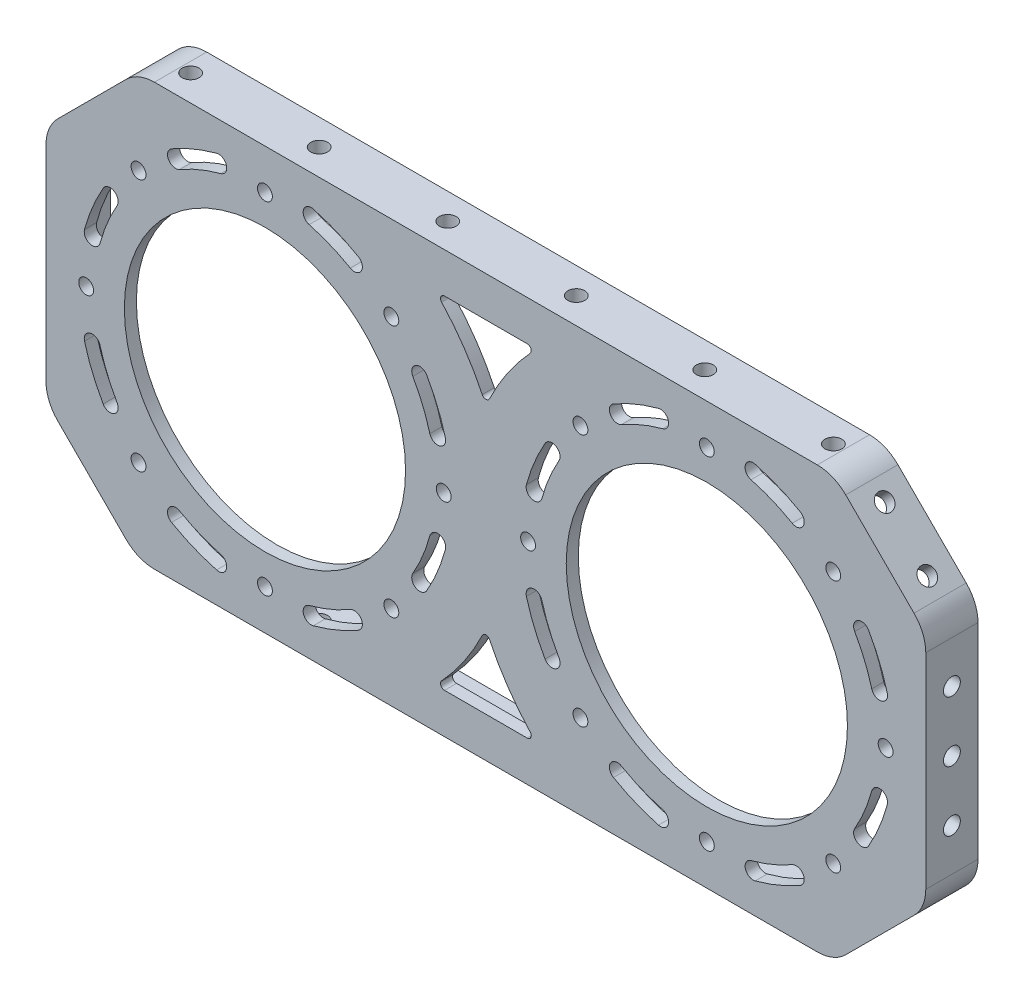
SolidWorks part; units mm, degrees
material "6061 合金"
ref_plane "前视基准面" through (0, 0, 0) normal (0, 0, 1) x (1, 0, 0)
ref_plane "上视基准面" through (0, 0, 0) normal (0, 1, 0) x (1, 0, 0)
ref_plane "右视基准面" through (0, 0, 0) normal (1, 0, 0) x (0, 0, -1)
other "Configuration Table"
sketch "草图1" plane through (0, 0, 0) normal (0, 0, 1) x (1, 0, 0)
  line L0 (-125.5479, 60.1826) -> (-125.5479, -59.8174)
  line L1 (-125.5479, -59.8174) -> (124.4521, -59.8174)
  line L2 (124.4521, -59.8174) -> (124.4521, 60.1826)
  line L3 (124.4521, 60.1826) -> (-125.5479, 60.1826)
  circle A0 centre (54.4521, 42.6826) radius 1.85
  circle A1 centre (85.9183, 31.6489) radius 1.85
  circle A2 centre (98.9521, 0.1826) radius 1.85
  circle A3 centre (85.9183, -31.2836) radius 1.85
  circle A4 centre (22.9858, -31.2836) radius 1.85
  circle A5 centre (22.9858, 31.6489) radius 1.85
  circle A6 centre (54.4521, -42.3174) radius 1.85
  circle A7 centre (9.9521, 0.1826) radius 1.85
  circle A8 centre (54.4521, 0.1826) radius 35
  circle A9 centre (-55.5479, 0.1826) radius 35
  circle A10 centre (-87.0142, 31.6489) radius 1.85
  circle A11 centre (-11.0479, 0.1826) radius 1.85
  circle A12 centre (-55.5479, 42.6826) radius 1.85
  circle A13 centre (-24.0817, 31.6489) radius 1.85
  circle A14 centre (-24.0817, -31.2836) radius 1.85
  circle A15 centre (-55.5479, -42.3174) radius 1.85
  circle A16 centre (-87.0142, -31.2836) radius 1.85
  circle A17 centre (-100.0479, 0.1826) radius 1.85
extrude "凸台-拉伸1" add sketch "草图1" along normal blind 3
sketch "草图2" plane through (0, 0, 3) normal (0, 0, 1) x (1, 0, 0)
  line L0 (-0.5479, 60.1826) -> (-0.5479, -59.8174) construction
  line L1 (-87.1936, 52.6826) -> (-110.0479, 29.8283)
  line L2 (-110.0479, -52.3174) -> (108.9521, -52.3174)
  line L3 (-110.0479, -52.3174) -> (-110.0479, 52.6826)
  line L4 (124.4521, 60.1826) -> (-125.5479, 60.1826)
  line L5 (-125.5479, 60.1826) -> (-125.5479, -59.8174)
  line L6 (-125.5479, -59.8174) -> (124.4521, -59.8174)
  line L7 (124.4521, -59.8174) -> (124.4521, 60.1826)
  line L8 (124.4521, 60.1826) -> (-125.5479, 60.1826)
  line L9 (-125.5479, 60.1826) -> (-125.5479, -59.8174)
  line L10 (-125.5479, -59.8174) -> (124.4521, -59.8174)
  line L11 (124.4521, -59.8174) -> (124.4521, 60.1826)
  line L12 (-110.0479, 52.6826) -> (108.9521, 52.6826)
  line L13 (108.9521, -52.3174) -> (108.9521, 52.6826)
  line L14 (-0.5479, 52.6826) -> (-0.5479, -52.3174) construction
  line L15 (-110.0479, 0.1826) -> (108.9521, 0.1826) construction
  line L16 (-110.0479, -29.4631) -> (-87.1936, -52.3174)
  line L17 (86.0978, 52.6826) -> (108.9521, 29.8283)
  line L18 (108.9521, -29.4631) -> (86.0978, -52.3174)
  circle A0 centre (-55.5479, 42.6826) radius 1.85 construction
  circle A1 centre (-55.5479, -42.3174) radius 1.85 construction
  circle A2 centre (-100.0479, 0.1826) radius 1.85 construction
  circle A3 centre (-87.0142, 31.6489) radius 1.85 construction
  circle A4 centre (-87.0142, -31.2836) radius 1.85 construction
  circle A5 centre (85.9183, 31.6489) radius 1.85 construction
  circle A6 centre (85.9183, -31.2836) radius 1.85 construction
  point P6 (-0.5479, 0.1826)
  line M23 (124.4521, 60.1826) -> (-125.5479, 60.1826)
  line M24 (-125.5479, 60.1826) -> (-125.5479, -59.8174)
  line M25 (-125.5479, -59.8174) -> (124.4521, -59.8174)
  line M26 (124.4521, -59.8174) -> (124.4521, 60.1826)
  dimension "D2" = 10
  dimension "D4" = 10
  dimension "D6" = 15
  dimension "D10" = 15
  dimension "D3" = 10
  dimension "D5" = 45
  dimension "D7" = 45
  dimension "D8" = 45
  dimension "D9" = 45
  dimension "D11" = 15
  dimension "D12" = 15
  dimension "D1" = 0
extrude "切除-拉伸1" cut sketch "草图2" against normal through all contours L13 L2 L3 L12 M26 M23 M24 M25 | L12 L3 L1 | L16 L3 L2 | L13 L18 L2 | L12 L17 L13
sketch "草图3" plane through (0, 0, 0) normal (0, 0, -1) x (-1, 0, 0)
  line L0 (-105.9521, 28.5857) -> (-105.9521, -28.2204)
  line L1 (-105.9521, -28.2204) -> (-84.8551, -49.3174)
  line L2 (-84.8551, -49.3174) -> (85.951, -49.3174)
  line L3 (85.951, -49.3174) -> (107.0479, -28.2204)
  line L4 (107.0479, -28.2204) -> (107.0479, 28.5857)
  line L5 (107.0479, 28.5857) -> (85.951, 49.6826)
  line L6 (85.951, 49.6826) -> (-84.8551, 49.6826)
  line L7 (-84.8551, 49.6826) -> (-105.9521, 28.5857)
  line L8 (-108.9521, 29.8283) -> (-108.9521, -29.4631)
  line L9 (-108.9521, -29.4631) -> (-86.0978, -52.3174)
  line L10 (-86.0978, -52.3174) -> (87.1936, -52.3174)
  line L11 (87.1936, -52.3174) -> (110.0479, -29.4631)
  line L12 (110.0479, -29.4631) -> (110.0479, 29.8283)
  line L13 (110.0479, 29.8283) -> (87.1936, 52.6826)
  line L14 (87.1936, 52.6826) -> (-86.0978, 52.6826)
  line L15 (-86.0978, 52.6826) -> (-108.9521, 29.8283)
  line L16 (-108.9521, 29.8283) -> (-108.9521, -29.4631)
  line L17 (-108.9521, -29.4631) -> (-86.0978, -52.3174)
  line L18 (-86.0978, -52.3174) -> (87.1936, -52.3174)
  line L19 (87.1936, -52.3174) -> (110.0479, -29.4631)
  line L20 (110.0479, -29.4631) -> (110.0479, 29.8283)
  line L21 (110.0479, 29.8283) -> (87.1936, 52.6826)
  line L22 (87.1936, 52.6826) -> (-86.0978, 52.6826)
  line L23 (-86.0978, 52.6826) -> (-108.9521, 29.8283)
  dimension "D1" = 0
  dimension "D2" = 3
extrude "凸台-拉伸2" add sketch "草图3" along normal blind 10
sketch "草图5" plane through (0, 0, 0) normal (0, 0, -1) x (-1, 0, 0)
  line L8 (85.951, 49.6826) -> (-84.8551, 49.6826)
  line L9 (-84.8551, 49.6826) -> (-105.9521, 28.5857)
  line L10 (-105.9521, 28.5857) -> (-105.9521, -28.2204)
  line L11 (-105.9521, -28.2204) -> (-84.8551, -49.3174)
  line L12 (-84.8551, -49.3174) -> (85.951, -49.3174)
  line L13 (85.951, -49.3174) -> (107.0479, -28.2204)
  line L14 (107.0479, -28.2204) -> (107.0479, 28.5857)
  line L15 (107.0479, 28.5857) -> (85.951, 49.6826)
  line L16 (85.951, 49.6826) -> (-84.8551, 49.6826)
  line L17 (-84.8551, 49.6826) -> (-105.9521, 28.5857)
  line L18 (-105.9521, 28.5857) -> (-105.9521, -28.2204)
  line L19 (-105.9521, -28.2204) -> (-84.8551, -49.3174)
  line L20 (-84.8551, -49.3174) -> (85.951, -49.3174)
  line L21 (85.951, -49.3174) -> (107.0479, -28.2204)
  line L22 (107.0479, -28.2204) -> (107.0479, 28.5857)
  line L23 (107.0479, 28.5857) -> (85.951, 49.6826)
  circle A1 centre (-54.4521, 42.6826) radius 1.85
  circle A2 centre (-54.4521, 42.6826) radius 1.85
  circle A3 centre (-85.9183, 31.6489) radius 1.85
  circle A4 centre (-85.9183, 31.6489) radius 1.85
  circle A5 centre (-98.9521, 0.1826) radius 1.85
  circle A6 centre (-98.9521, 0.1826) radius 1.85
  circle A7 centre (-85.9183, -31.2836) radius 1.85
  circle A8 centre (-85.9183, -31.2836) radius 1.85
  circle A9 centre (-22.9858, -31.2836) radius 1.85
  circle A10 centre (-22.9858, -31.2836) radius 1.85
  circle A11 centre (-22.9858, 31.6489) radius 1.85
  circle A12 centre (-22.9858, 31.6489) radius 1.85
  circle A13 centre (-54.4521, -42.3174) radius 1.85
  circle A14 centre (-54.4521, -42.3174) radius 1.85
  circle A15 centre (-9.9521, 0.1826) radius 1.85
  circle A16 centre (-9.9521, 0.1826) radius 1.85
  circle A17 centre (-54.4521, 0.1826) radius 35
  circle A18 centre (-54.4521, 0.1826) radius 35
  circle A19 centre (55.5479, 0.1826) radius 35
  circle A20 centre (55.5479, 0.1826) radius 35
  circle A21 centre (87.0142, 31.6489) radius 1.85
  circle A22 centre (87.0142, 31.6489) radius 1.85
  circle A23 centre (11.0479, 0.1826) radius 1.85
  circle A24 centre (11.0479, 0.1826) radius 1.85
  circle A25 centre (55.5479, 42.6826) radius 1.85
  circle A26 centre (55.5479, 42.6826) radius 1.85
  circle A27 centre (24.0817, 31.6489) radius 1.85
  circle A28 centre (24.0817, 31.6489) radius 1.85
  circle A29 centre (24.0817, -31.2836) radius 1.85
  circle A30 centre (24.0817, -31.2836) radius 1.85
  circle A31 centre (55.5479, -42.3174) radius 1.85
  circle A32 centre (55.5479, -42.3174) radius 1.85
  circle A33 centre (87.0142, -31.2836) radius 1.85
  circle A34 centre (87.0142, -31.2836) radius 1.85
  circle A35 centre (100.0479, 0.1826) radius 1.85
  circle A36 centre (100.0479, 0.1826) radius 1.85
  dimension "D1" = 0
  dimension "D2" = 0
  dimension "D3" = 0
  dimension "D4" = 0
  dimension "D5" = 0
  dimension "D6" = 0
  dimension "D7" = 0
  dimension "D8" = 0
  dimension "D9" = 0
  dimension "D10" = 0
  dimension "D11" = 0
  dimension "D12" = 0
  dimension "D13" = 0
  dimension "D14" = 0
  dimension "D15" = 0
  dimension "D16" = 0
  dimension "D17" = 0
  dimension "D18" = 0
  dimension "D19" = 0
sketch "草图6" plane through (69.3902, 69.3902, 0) normal (0.7071, 0.7071, 0) x (0, 0, -1)
  line L0 (3.5, -23.6281) -> (3.5, -55.9489) construction
  line L1 (-3, -39.7885) -> (10, -39.7885)
  line L4 (10, -23.6281) -> (-3, -23.6281)
  line L5 (-3, -23.6281) -> (-3, -55.9489)
  line L6 (-3, -55.9489) -> (10, -55.9489)
  line L7 (10, -55.9489) -> (10, -23.6281)
  line L8 (10, -23.6281) -> (-3, -23.6281) construction
  line L9 (-3, -23.6281) -> (-3, -55.9489) construction
  line L10 (-3, -55.9489) -> (10, -55.9489) construction
  line L11 (10, -55.9489) -> (10, -23.6281) construction
  circle A0 centre (3.5, -32.2885) radius 2.1
  circle A1 centre (3.5, -47.2885) radius 2.1
  dimension "D2" = 4.2
  dimension "D3" = 4.2
  dimension "D5" = 7.5
  dimension "D4" = 15
  dimension "D1" = 0
extrude "切除-拉伸2" cut sketch "草图6" against normal blind 5 contours A0 | A1
sketch "草图7" plane through (108.9521, 0, 0) normal (1, 0, 0) x (0, 0, -1)
  line L0 (3.5, 29.8283) -> (3.5, -29.4631) construction
  line L1 (-3, 0.1826) -> (10, 0.1826) construction
  line L4 (-3, -29.4631) -> (10, -29.4631)
  line L5 (10, -29.4631) -> (10, 29.8283)
  line L6 (10, 29.8283) -> (-3, 29.8283)
  line L7 (-3, 29.8283) -> (-3, -29.4631)
  line L8 (-3, -29.4631) -> (10, -29.4631) construction
  line L9 (10, -29.4631) -> (10, 29.8283) construction
  line L10 (10, 29.8283) -> (-3, 29.8283) construction
  line L11 (-3, 29.8283) -> (-3, -29.4631) construction
  circle A0 centre (3.5, 15.1826) radius 2.1
  circle A1 centre (3.5, 0.1826) radius 2.1
  circle A2 centre (3.5, -14.8174) radius 2.1
  dimension "D2" = 4.2
  dimension "D4" = 15
  dimension "D1" = 0
  dimension "D3" = 3
extrude "切除-拉伸3" cut sketch "草图7" against normal through all
sketch "草图8" plane through (69.2076, -69.2076, 0) normal (0.7071, -0.7071, 0) x (0, 0, -1)
  line L0 (3.5, 56.2072) -> (3.5, 23.8864) construction
  line L1 (10, 56.2072) -> (-3, 56.2072) construction
  line L2 (-3, 40.0468) -> (10, 40.0468) construction
  line L4 (10, 56.2072) -> (-3, 56.2072)
  line L5 (-3, 56.2072) -> (-3, 23.8864)
  line L6 (-3, 23.8864) -> (10, 23.8864)
  line L7 (10, 23.8864) -> (10, 56.2072)
  line L8 (10, 56.2072) -> (-3, 56.2072)
  line L9 (-3, 56.2072) -> (-3, 23.8864)
  line L10 (-3, 23.8864) -> (10, 23.8864)
  line L11 (10, 23.8864) -> (10, 56.2072)
  circle A0 centre (3.5, 47.5468) radius 2.1
  circle A1 centre (3.5, 32.5468) radius 2.1
  dimension "D2" = 4.2
  dimension "D3" = 4.2
  dimension "D4" = 7.5
  dimension "D5" = 7.5
  dimension "D1" = 0
extrude "切除-拉伸4" cut sketch "草图8" against normal blind 5 contours A0 | A1
sketch "草图9" plane through (0, -52.3174, 0) normal (0, -1, 0) x (1, 0, 0)
  line L0 (-87.1936, -3.5) -> (86.0978, -3.5) construction
  line L1 (-0.5479, 3) -> (-0.5479, -10) construction
  line L4 (-87.1936, 3) -> (-87.1936, -10)
  line L5 (-87.1936, -10) -> (86.0978, -10)
  line L6 (86.0978, -10) -> (86.0978, 3)
  line L7 (86.0978, 3) -> (-87.1936, 3)
  line L8 (-87.1936, 3) -> (-87.1936, -10) construction
  line L9 (-87.1936, -10) -> (86.0978, -10) construction
  line L10 (86.0978, -10) -> (86.0978, 3) construction
  line L11 (86.0978, 3) -> (-87.1936, 3) construction
  circle A0 centre (-80.5479, -3.5) radius 2.1
  circle A1 centre (-64.5479, -3.5) radius 2.1 construction
  circle A2 centre (-48.5479, -3.5) radius 2.1
  circle A3 centre (-32.5479, -3.5) radius 2.1 construction
  circle A4 centre (-16.5479, -3.5) radius 2.1
  circle A5 centre (-0.5479, -3.5) radius 2.1 construction
  circle A6 centre (15.4521, -3.5) radius 2.1
  circle A7 centre (31.4521, -3.5) radius 2.1 construction
  circle A8 centre (47.4521, -3.5) radius 2.1
  circle A9 centre (63.4521, -3.5) radius 2.1 construction
  circle A10 centre (79.4521, -3.5) radius 2.1
  dimension "D2" = 4.2
  dimension "D4" = 16
  dimension "D1" = 0
  dimension "D3" = 11
sketch "草图10" plane through (-69.7555, -69.7555, 0) normal (-0.7071, -0.7071, 0) x (0, 0, 1)
  line L0 (-3.5, 56.9821) -> (-3.5, 24.6612) construction
  line L1 (-10, 40.8217) -> (3, 40.8217) construction
  line L4 (3, 56.9821) -> (-10, 56.9821)
  line L5 (-10, 56.9821) -> (-10, 24.6612)
  line L6 (-10, 24.6612) -> (3, 24.6612)
  line L7 (3, 24.6612) -> (3, 56.9821)
  line L8 (3, 56.9821) -> (-10, 56.9821) construction
  line L9 (-10, 56.9821) -> (-10, 24.6612) construction
  line L10 (-10, 24.6612) -> (3, 24.6612) construction
  line L11 (3, 24.6612) -> (3, 56.9821) construction
  circle A0 centre (-3.5, 48.3217) radius 2.1
  circle A1 centre (-3.5, 33.3217) radius 2.1
  dimension "D2" = 4.2
  dimension "D3" = 4.2
  dimension "D4" = 7.5
  dimension "D5" = 7.5
  dimension "D1" = 0
extrude "切除-拉伸6" cut sketch "草图10" against normal blind 5
sketch "草图11" plane through (-69.9381, 69.9381, 0) normal (-0.7071, 0.7071, 0) x (0, 0, 1)
  line L0 (-3.5, -24.403) -> (-3.5, -56.7238) construction
  line L1 (-10, -56.7238) -> (3, -56.7238) construction
  line L2 (-10, -40.5634) -> (3, -40.5634) construction
  line L4 (3, -24.403) -> (-10, -24.403)
  line L5 (-10, -24.403) -> (-10, -56.7238)
  line L6 (-10, -56.7238) -> (3, -56.7238)
  line L7 (3, -56.7238) -> (3, -24.403)
  line L8 (3, -24.403) -> (-10, -24.403) construction
  line L9 (-10, -24.403) -> (-10, -56.7238) construction
  line L10 (-10, -56.7238) -> (3, -56.7238) construction
  line L11 (3, -56.7238) -> (3, -24.403) construction
  circle A0 centre (-3.5, -33.0634) radius 2.1
  circle A1 centre (-3.5, -48.0634) radius 2.1
  dimension "D2" = 4.2
  dimension "D3" = 4.2
  dimension "D4" = 7.5
  dimension "D5" = 7.5
  dimension "D1" = 0
extrude "切除-拉伸7" cut sketch "草图11" against normal blind 5
fillet "圆角1" radius 10 16 edges at (-85.951, -49.3174, -5) (-107.0479, -28.2204, -5) (-107.0479, 28.5857, -5) (-85.951, 49.6826, -5) (84.8551, -49.3174, -5) (105.9521, -28.2204, -5) (105.9521, 28.5857, -5) (84.8551, 49.6826, -5) (-87.1936, 52.6826, -3.5) (-110.0479, 29.8283, -3.5) (-110.0479, -29.4631, -3.5) (-87.1936, -52.3174, -3.5) (86.0978, -52.3174, -3.5) (108.9521, -29.4631, -3.5) (108.9521, 29.8283, -3.5) (86.0978, 52.6826, -3.5)
extrude "切除-拉伸8" cut sketch "草图9" against normal blind 250
sketch "草图12" plane through (0, 0, 3) normal (0, 0, 1) x (1, 0, 0)
  line L0 (-94.086, 22.4326) -> (-55.5479, 0.1826) construction
  line L1 (-55.5479, 0.1826) -> (-87.0142, 31.6489) construction
  line L2 (-55.5479, 0.1826) -> (-98.5316, 11.7001) construction
  line L3 (-55.5479, 0.1826) -> (-100.0479, 0.1826) construction
  line L4 (-0.5479, 52.6826) -> (-0.5479, -52.3174) construction
  line L5 (-83.0515, 52.6826) -> (81.9557, 52.6826) construction
  line L6 (-83.0515, -52.3174) -> (81.9557, -52.3174) construction
  line L7 (-20.6373, 42.6826) -> (19.5415, 42.6826)
  line L8 (-13.1952, -42.3174) -> (12.0994, -42.3174)
  circle A0 centre (-55.5479, 0.1826) radius 35 construction
  circle A1 centre (-55.5479, 0.1826) radius 35 construction
  circle A2 centre (-55.5479, 0.1826) radius 44.5 construction
  arc A3 (-98.5316, 11.7001) -> (-94.086, 22.4326) centre (-55.5479, 0.1826) cw construction
  arc A4 (-95.8181, 23.4326) -> (-100.4635, 12.2177) centre (-55.5479, 0.1826) ccw
  arc A5 (-92.354, 21.4326) -> (-96.5998, 11.1824) centre (-55.5479, 0.1826) ccw
  arc A6 (-92.354, 21.4326) -> (-95.8181, 23.4326) centre (-94.086, 22.4326) ccw
  arc A7 (-100.4635, 12.2177) -> (-96.5998, 11.1824) centre (-98.5316, 11.7001) ccw
  arc A8 (76.7021, 38.7208) -> (65.9695, 43.1663) centre (54.4521, 0.1826) ccw construction
  arc A9 (66.4872, 45.0982) -> (77.7021, 40.4528) centre (54.4521, 0.1826) cw
  arc A10 (-66.5477, 41.2345) -> (-76.7979, 36.9887) centre (-55.5479, 0.1826) ccw
  arc A11 (-66.5477, 41.2345) -> (-67.583, 45.0982) centre (-67.0654, 43.1663) ccw
  arc A12 (-78.7979, 40.4528) -> (-76.7979, 36.9887) centre (-77.7979, 38.7208) ccw
  arc A13 (-67.583, 45.0982) -> (-78.7979, 40.4528) centre (-55.5479, 0.1826) ccw
  arc A14 (-77.7979, 38.7208) -> (-67.0654, 43.1663) centre (-55.5479, 0.1826) cw construction
  arc A15 (-34.2979, 36.9887) -> (-44.5481, 41.2345) centre (-55.5479, 0.1826) ccw
  arc A16 (-34.2979, 36.9887) -> (-32.2979, 40.4528) centre (-33.2979, 38.7208) ccw
  arc A17 (-43.5128, 45.0982) -> (-44.5481, 41.2345) centre (-44.0305, 43.1663) ccw
  arc A18 (-32.2979, 40.4528) -> (-43.5128, 45.0982) centre (-55.5479, 0.1826) ccw
  arc A19 (-44.0305, 43.1663) -> (-33.2979, 38.7208) centre (-55.5479, 0.1826) cw construction
  arc A20 (-14.4961, 11.1824) -> (-18.7418, 21.4326) centre (-55.5479, 0.1826) ccw
  arc A21 (-14.4961, 11.1824) -> (-10.6324, 12.2177) centre (-12.5642, 11.7001) ccw
  arc A22 (-15.2777, 23.4326) -> (-18.7418, 21.4326) centre (-17.0098, 22.4326) ccw
  arc A23 (-10.6324, 12.2177) -> (-15.2777, 23.4326) centre (-55.5479, 0.1826) ccw
  arc A24 (-17.0098, 22.4326) -> (-12.5642, 11.7001) centre (-55.5479, 0.1826) cw construction
  arc A25 (-18.7418, -21.0674) -> (-14.4961, -10.8172) centre (-55.5479, 0.1826) ccw
  arc A26 (-18.7418, -21.0674) -> (-15.2777, -23.0674) centre (-17.0098, -22.0674) ccw
  arc A27 (-10.6324, -11.8524) -> (-14.4961, -10.8172) centre (-12.5642, -11.3348) ccw
  arc A28 (-15.2777, -23.0674) -> (-10.6324, -11.8524) centre (-55.5479, 0.1826) ccw
  arc A29 (-12.5642, -11.3348) -> (-17.0098, -22.0674) centre (-55.5479, 0.1826) cw construction
  arc A30 (-44.5481, -40.8692) -> (-34.2979, -36.6234) centre (-55.5479, 0.1826) ccw
  arc A31 (-44.5481, -40.8692) -> (-43.5128, -44.7329) centre (-44.0305, -42.8011) ccw
  arc A32 (-32.2979, -40.0875) -> (-34.2979, -36.6234) centre (-33.2979, -38.3555) ccw
  arc A33 (-43.5128, -44.7329) -> (-32.2979, -40.0875) centre (-55.5479, 0.1826) ccw
  arc A34 (-33.2979, -38.3555) -> (-44.0305, -42.8011) centre (-55.5479, 0.1826) cw construction
  arc A35 (-76.7979, -36.6234) -> (-66.5477, -40.8692) centre (-55.5479, 0.1826) ccw
  arc A36 (-76.7979, -36.6234) -> (-78.7979, -40.0875) centre (-77.7979, -38.3555) ccw
  arc A37 (-67.583, -44.7329) -> (-66.5477, -40.8692) centre (-67.0654, -42.8011) ccw
  arc A38 (-78.7979, -40.0875) -> (-67.583, -44.7329) centre (-55.5479, 0.1826) ccw
  arc A39 (-67.0654, -42.8011) -> (-77.7979, -38.3555) centre (-55.5479, 0.1826) cw construction
  arc A40 (-96.5998, -10.8172) -> (-92.354, -21.0674) centre (-55.5479, 0.1826) ccw
  arc A41 (-96.5998, -10.8172) -> (-100.4635, -11.8524) centre (-98.5316, -11.3348) ccw
  arc A42 (-95.8181, -23.0674) -> (-92.354, -21.0674) centre (-94.086, -22.0674) ccw
  arc A43 (-100.4635, -11.8524) -> (-95.8181, -23.0674) centre (-55.5479, 0.1826) ccw
  arc A44 (-94.086, -22.0674) -> (-98.5316, -11.3348) centre (-55.5479, 0.1826) cw construction
  arc A45 (65.4519, 41.2345) -> (75.7021, 36.9887) centre (54.4521, 0.1826) cw
  arc A46 (65.4519, 41.2345) -> (66.4872, 45.0982) centre (65.9695, 43.1663) cw
  arc A47 (77.7021, 40.4528) -> (75.7021, 36.9887) centre (76.7021, 38.7208) cw
  arc A48 (42.9346, 43.1663) -> (32.2021, 38.7208) centre (54.4521, 0.1826) ccw construction
  arc A49 (31.2021, 40.4528) -> (42.417, 45.0982) centre (54.4521, 0.1826) cw
  arc A50 (33.2021, 36.9887) -> (43.4523, 41.2345) centre (54.4521, 0.1826) cw
  arc A51 (33.2021, 36.9887) -> (31.2021, 40.4528) centre (32.2021, 38.7208) cw
  arc A52 (42.417, 45.0982) -> (43.4523, 41.2345) centre (42.9346, 43.1663) cw
  arc A53 (15.914, 22.4326) -> (11.4684, 11.7001) centre (54.4521, 0.1826) ccw construction
  arc A54 (9.5365, 12.2177) -> (14.1819, 23.4326) centre (54.4521, 0.1826) cw
  arc A55 (13.4002, 11.1824) -> (17.646, 21.4326) centre (54.4521, 0.1826) cw
  arc A56 (13.4002, 11.1824) -> (9.5365, 12.2177) centre (11.4684, 11.7001) cw
  arc A57 (14.1819, 23.4326) -> (17.646, 21.4326) centre (15.914, 22.4326) cw
  arc A58 (11.4684, -11.3348) -> (15.914, -22.0674) centre (54.4521, 0.1826) ccw construction
  arc A59 (14.1819, -23.0674) -> (9.5365, -11.8524) centre (54.4521, 0.1826) cw
  arc A60 (17.646, -21.0674) -> (13.4002, -10.8172) centre (54.4521, 0.1826) cw
  arc A61 (17.646, -21.0674) -> (14.1819, -23.0674) centre (15.914, -22.0674) cw
  arc A62 (9.5365, -11.8524) -> (13.4002, -10.8172) centre (11.4684, -11.3348) cw
  arc A63 (32.2021, -38.3555) -> (42.9346, -42.8011) centre (54.4521, 0.1826) ccw construction
  arc A64 (42.417, -44.7329) -> (31.2021, -40.0875) centre (54.4521, 0.1826) cw
  arc A65 (43.4523, -40.8692) -> (33.2021, -36.6234) centre (54.4521, 0.1826) cw
  arc A66 (43.4523, -40.8692) -> (42.417, -44.7329) centre (42.9346, -42.8011) cw
  arc A67 (31.2021, -40.0875) -> (33.2021, -36.6234) centre (32.2021, -38.3555) cw
  arc A68 (65.9695, -42.8011) -> (76.7021, -38.3555) centre (54.4521, 0.1826) ccw construction
  arc A69 (77.7021, -40.0875) -> (66.4872, -44.7329) centre (54.4521, 0.1826) cw
  arc A70 (75.7021, -36.6234) -> (65.4519, -40.8692) centre (54.4521, 0.1826) cw
  arc A71 (75.7021, -36.6234) -> (77.7021, -40.0875) centre (76.7021, -38.3555) cw
  arc A72 (66.4872, -44.7329) -> (65.4519, -40.8692) centre (65.9695, -42.8011) cw
  arc A73 (97.4358, 11.7001) -> (92.9902, 22.4326) centre (54.4521, 0.1826) ccw construction
  arc A74 (94.7223, 23.4326) -> (99.3676, 12.2177) centre (54.4521, 0.1826) cw
  arc A75 (91.2582, 21.4326) -> (95.5039, 11.1824) centre (54.4521, 0.1826) cw
  arc A76 (91.2582, 21.4326) -> (94.7223, 23.4326) centre (92.9902, 22.4326) cw
  arc A77 (99.3676, 12.2177) -> (95.5039, 11.1824) centre (97.4358, 11.7001) cw
  arc A78 (92.9902, -22.0674) -> (97.4358, -11.3348) centre (54.4521, 0.1826) ccw construction
  arc A79 (99.3676, -11.8524) -> (94.7223, -23.0674) centre (54.4521, 0.1826) cw
  arc A80 (95.5039, -10.8172) -> (91.2582, -21.0674) centre (54.4521, 0.1826) cw
  arc A81 (95.5039, -10.8172) -> (99.3676, -11.8524) centre (97.4358, -11.3348) cw
  arc A82 (94.7223, -23.0674) -> (91.2582, -21.0674) centre (92.9902, -22.0674) cw
  circle A83 centre (54.4521, 0.1826) radius 44.5 construction
  circle A84 centre (54.4521, 0.1826) radius 55
  circle A85 centre (-55.5479, 0.1826) radius 55
  circle A86 centre (54.4521, 0.1826) radius 60
  circle A87 centre (-55.5479, 0.1826) radius 60
  point P8 (-96.6606, 17.2121)
  point P22 (-72.5773, 41.2953)
  point P29 (-38.5185, 41.2953)
  point P36 (-14.4353, 17.2121)
  point P43 (-14.4353, -16.8468)
  point P50 (-38.5185, -40.93)
  point P57 (-72.5773, -40.93)
  point P64 (-96.6606, -16.8468)
  point P69 (-55.5479, 0.1826)
  point P76 (71.4815, 41.2953)
  point P84 (37.4227, 41.2953)
  point P92 (13.3394, 17.2121)
  point P100 (13.3394, -16.8468)
  point P108 (37.4227, -40.93)
  point P116 (71.4815, -40.93)
  point P124 (95.5647, 17.2121)
  point P132 (95.5647, -16.8468)
  dimension "D1" = 15
  dimension "D2" = 15
  dimension "D3" = 2
  dimension "D6" = 5
  dimension "D7" = 5
  dimension "D5" = 10
  dimension "D8" = 10
  dimension "D4" = 8
extrude "切除-拉伸9" cut sketch "草图12" against normal blind 250 contours A87 A86 L7 | A87 L8 A86 | A13 A12 A10 A11 | A18 A17 A15 A16 | A5 A7 A4 A6 | A43 A42 A40 A41 | A38 A37 A35 A36 | A33 A32 A30 A31 | A28 A27 A25 A26 | A23 A22 A20 A21 | A54 A57 A55 A56 | A49 A52 A50 A51 | A9 A47 A45 A46 | A59 A62 A60 A61 | A64 A67 A65 A66 | A69 A72 A70 A71 | A79 A82 A80 A81 | A74 A77 A75 A76
fillet "圆角2" radius 1 1 edges at (-13.1952, 42.6826, 1.5)
fillet "圆角3" radius 1 1 edges at (12.0994, 42.6826, 1.5)
fillet "圆角4" radius 1 1 edges at (-0.5479, 24.1618, 1.5)
fillet "圆角5" radius 1 1 edges at (-0.5479, -23.7965, 1.5)
fillet "圆角6" radius 1 1 edges at (-13.1952, -42.3174, 1.5)
fillet "圆角7" radius 1 1 edges at (12.0994, -42.3174, 1.5)
